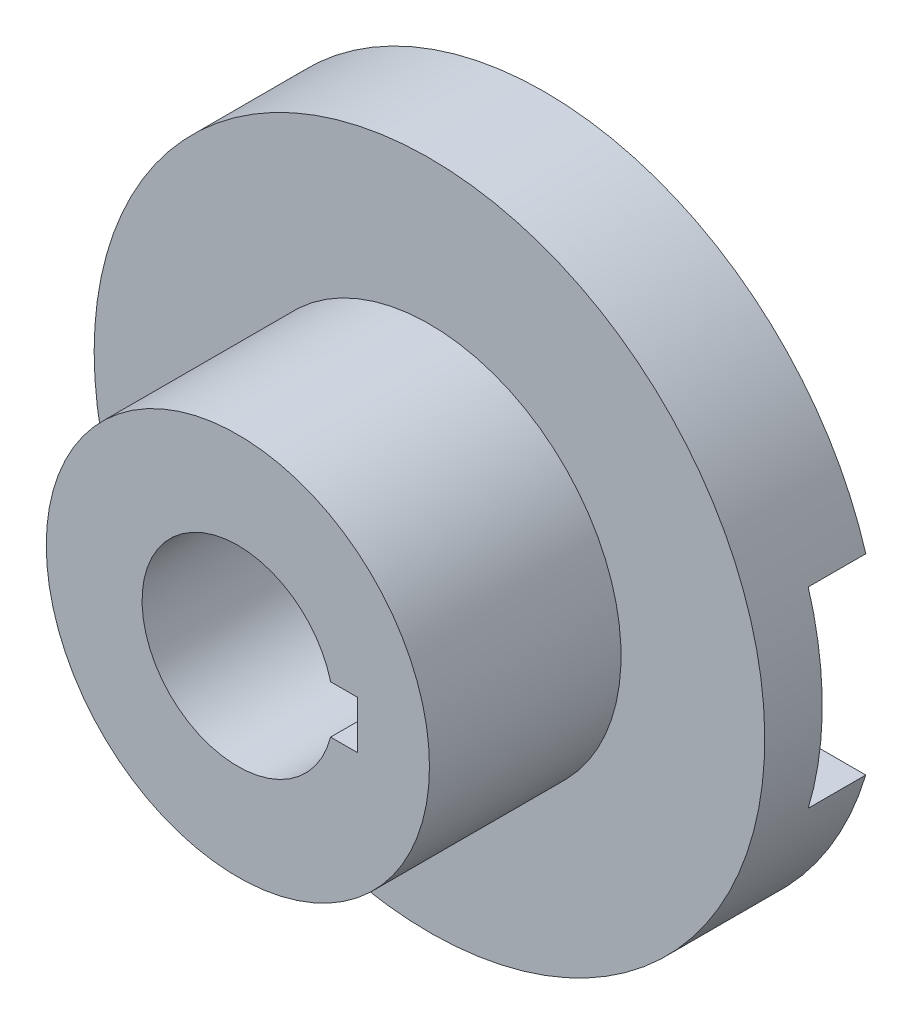
SolidWorks part; units mm, degrees
ref_plane "Front Plane" through (0, 0, 0) normal (0, 0, 1) x (1, 0, 0)
ref_plane "Top Plane" through (0, 0, 0) normal (0, 1, 0) x (1, 0, 0)
ref_plane "Right Plane" through (0, 0, 0) normal (1, 0, 0) x (0, 0, -1)
sketch "Sketch1" plane through (0, 0, 0) normal (0, 0, 1) x (1, 0, 0)
  line L0 (0, 31.747) -> (0, -31.747) construction
  line L1 (-45.8259, 0) -> (45.8259, 0) construction
  circle A0 centre (0, 0) radius 5
  circle A1 centre (0, 0) radius 10
  point P4 (0, 0)
  point P7 (0, 0)
  dimension "D1" = 10
  dimension "D2" = 20
extrude "Boss-Extrude1" add sketch "Sketch1" along normal mid plane 10
sketch "Sketch3" plane through (0, 0, -5) normal (0, 0, -1) x (-1, 0, 0)
  circle A0 centre (0, 0) radius 5
  circle A1 centre (0, 0) radius 17.5
  dimension "D1" = 10
  dimension "D2" = 35
extrude "Boss-Extrude2" add sketch "Sketch3" along normal blind 6
sketch "Sketch4" plane through (0, 0, -11) normal (0, 0, -1) x (-1, 0, 0)
  line L0 (-17.5, 0) -> (17.5, 0) construction
  line L1 (-16.7705, -5) -> (16.7705, -5)
  line L2 (-16.7705, 5) -> (16.7705, 5)
  line L3 (-17.5, 5) -> (17.5, 5) construction
  line L4 (-17.5, -5) -> (17.5, -5) construction
  circle A0 centre (0, 0) radius 17.5 construction
  arc A1 (-16.7705, 5) -> (-16.7705, -5) centre (0, 0) ccw
  arc A2 (16.7705, -5) -> (16.7705, 5) centre (0, 0) ccw
  dimension "D1" = 5
  dimension "D2" = 5
extrude "Cut-Extrude1" cut sketch "Sketch4" against normal blind 3
sketch "Sketch5" plane through (0, 0, 5) normal (0, 0, 1) x (1, 0, 0)
  line L0 (0, 17.5) -> (0, -17.5) construction
  line L1 (-17.5, 0) -> (17.5, 0) construction
  line L3 (3.75, 1.25) -> (6.25, 1.25)
  line L4 (3.75, 1.25) -> (3.75, -1.25)
  line L5 (3.75, -1.25) -> (6.25, -1.25)
  line L6 (6.25, 1.25) -> (6.25, -1.25)
  line L7 (3.75, 1.25) -> (6.25, -1.25) construction
  line L8 (3.75, -1.25) -> (6.25, 1.25) construction
  circle A0 centre (0, 0) radius 17.5 construction
  circle A1 centre (0, 0) radius 5 construction
  circle A2 centre (0, 0) radius 5
  point P10 (5, 0)
  dimension "D1" = 2.5
  dimension "D2" = 2.5
extrude "Cut-Extrude2" cut sketch "Sketch5" against normal blind 10 contours L6 L5 L4 L3
